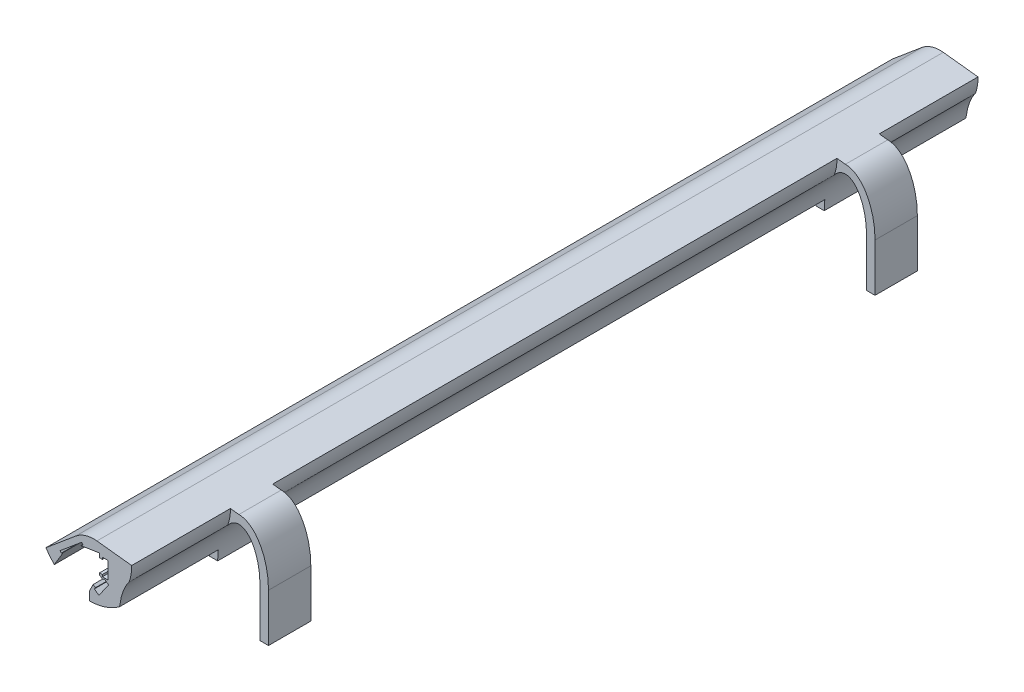
SolidWorks part; units mm, degrees
ref_plane "前视基准面" through (0, 0, 0) normal (0, 0, 1) x (1, 0, 0)
ref_plane "上视基准面" through (0, 0, 0) normal (0, 1, 0) x (1, 0, 0)
ref_plane "右视基准面" through (0, 0, 0) normal (1, 0, 0) x (0, 0, -1)
other "Configuration Table"
sketch "草图1" plane through (0, 0, 0) normal (0, 0, 1) x (1, 0, 0)
  line L0 (0, -18) -> (18, -18) construction
  line L1 (18, -18) -> (18, 0) construction
  line L2 (7.5, -18) -> (10.5, -18)
  line L4 (25.5, -18) -> (25.5, -34.9829)
  line L5 (25.5, -34.9829) -> (28.5, -34.9829)
  line L6 (28.5, -34.9829) -> (28.5, -18)
  line L7 (0, 0) -> (-11.4907, -9.6418)
  line L8 (0, 0) -> (0, -15)
  line L9 (5.2507, -8.584) -> (2.4359, -6.613) construction
  line L10 (0, 0) -> (15, 0) construction
  line L11 (1.8092, -13.4989) -> (-1.7004, -11.0414) construction
  line L12 (4.7829, -8.3) -> (-1.4748, -8.3) construction
  line L13 (4.6248, -8.3) -> (4.6248, -2.3)
  line L14 (4.6248, -8.3) -> (6.6248, -8.3)
  line L15 (4.6248, -2.3) -> (6.6248, -2.3)
  line L16 (6.6248, -8.3) -> (6.6248, -2.3)
  line L25 (5.1998, -8.5483) -> (1.7583, -13.4632)
  line L26 (5.1998, -8.5483) -> (6.8381, -9.6955)
  line L27 (1.7583, -13.4632) -> (3.3966, -14.6104)
  line L28 (6.8381, -9.6955) -> (3.3966, -14.6104)
  line L29 (4.7829, -2.3) -> (-0.818, -2.3) construction
  line L30 (2.1598, -12.8898) -> (1.3407, -12.3162)
  line L31 (1.3407, -12.3162) -> (0, -15)
  line L32 (4.6248, -7.6) -> (3.6248, -7.6)
  line L33 (3.6248, -7.6) -> (3.6248, -8.3)
  line L34 (3.6248, -8.3) -> (4.7983, -9.1217)
  line L35 (4.6248, -3) -> (3.6248, -3)
  line L36 (3.6248, -3) -> (3.6248, -1.5)
  line L37 (0, -15) -> (0, -18)
  line L38 (-9.9586, -8.3562) -> (-2.2981, -1.9284)
  line L39 (-9.9586, -8.3562) -> (-10.4085, -7.82)
  line L40 (-2.2981, -1.9284) -> (-2.7481, -1.3921)
  line L41 (-10.4085, -7.82) -> (-2.7481, -1.3921)
  line L42 (-15.3683, -9.371) -> (-4.8635, -0.5563)
  line L43 (2.6806, 1.7207) -> (18, 0)
  line L44 (-9.1925, -7.7135) -> (-12.3906, -13.0566)
  line L45 (-3.0642, -2.5712) -> (3.6248, -1.5)
  line L46 (4.7983, -9.1217) -> (6.0189, -9.1219)
  circle A0 centre (0, 0) radius 18
  circle A1 centre (0, 0) radius 15
  arc A2 (2.6806, 1.7207) -> (-4.8635, -0.5563) centre (1.5644, -8.2168) ccw
  ellipse E0 centre (18, -18) end of major axis (18, 0) minor radius 10.5 (7.5, -18) -> (28.5, -18) cw
  ellipse E1 centre (18, -18) end of major axis (18, -33) minor radius 7.5 (10.5, -18) -> (25.5, -18) cw
  point P61 (-1.5795, 2.1992)
  dimension "D1" = 30
  dimension "D2" = 3
  dimension "D30" = 10
  dimension "D3" = 3
  dimension "D4" = 15
  dimension "D5" = 15
  dimension "D6" = 50
  dimension "D7" = 35
  dimension "D8" = 0.7
  dimension "D9" = 6
  dimension "D10" = 2
  dimension "D11" = 6
  dimension "D12" = 2
  dimension "D13" = 0.7
  dimension "D14" = 0.7
  dimension "D15" = 0.7
  dimension "D16" = 1
  dimension "D17" = 1
  dimension "D18" = 1
  dimension "D19" = 1.5
  dimension "D20" = 0.7
  dimension "D21" = 3
  dimension "D22" = 0.7
  dimension "D23" = 10
  dimension "D24" = 3
  dimension "D25" = 130
  dimension "D26" = 1
  dimension "D27" = 1
  dimension "D28" = 2
  dimension "D29" = 18
extrude "凸台-拉伸7" add sketch "草图1" along normal blind 150 contours A1 L42 A0 L44 | L7 A1 L44 L38 | A1 E0 L43 A2 L42 L7 L39 L41 L40 L8 L45 L36 L35 L13 L15 L16 L14 L32 L33 L34 L25 L26 L28 | L7 L45 L8 | A1 E1 E0 | A0 E1 A1 E0 | A0 E0 A1 L37 | L31 A1 L27 L25 L30
sketch "草图5" plane through (0, 0, 0) normal (0, 0, 1) x (1, 0, 0)
  line L0 (-15.3683, -9.371) -> (-4.8635, -0.5563) construction
  line L1 (2.6806, 1.7207) -> (18, 0) construction
  line L2 (0, -15) -> (0, -18) construction
  line L3 (0, 0) -> (-11.4907, -9.6418) construction
  line L4 (7.5, -18) -> (10.5, -18)
  line L5 (28.5, -34.9829) -> (28.5, -18)
  line L6 (25.5, -34.9829) -> (28.5, -34.9829)
  line L7 (25.5, -18) -> (25.5, -34.9829)
  line L8 (7.5, -18) -> (10.5, -18)
  line L9 (28.5, -34.9829) -> (28.5, -18)
  line L10 (25.5, -34.9829) -> (28.5, -34.9829)
  line L11 (25.5, -18) -> (25.5, -34.9829)
  line L12 (5.1998, -8.5483) -> (1.7583, -13.4632)
  line L13 (1.7583, -13.4632) -> (3.3966, -14.6104)
  line L14 (3.3966, -14.6104) -> (6.8381, -9.6955)
  line L15 (6.8381, -9.6955) -> (5.1998, -8.5483)
  line L16 (5.1998, -8.5483) -> (1.7583, -13.4632)
  line L17 (1.7583, -13.4632) -> (3.3966, -14.6104)
  line L18 (3.3966, -14.6104) -> (6.8381, -9.6955)
  line L19 (6.8381, -9.6955) -> (5.1998, -8.5483)
  line L20 (6.6248, -8.3) -> (6.6248, -2.3)
  line L21 (6.6248, -2.3) -> (4.6248, -2.3)
  line L22 (4.6248, -2.3) -> (4.6248, -8.3)
  line L23 (4.6248, -8.3) -> (6.6248, -8.3)
  line L24 (6.6248, -8.3) -> (6.6248, -2.3)
  line L25 (6.6248, -2.3) -> (4.6248, -2.3)
  line L26 (4.6248, -2.3) -> (4.6248, -8.3)
  line L27 (4.6248, -8.3) -> (6.6248, -8.3)
  line L28 (-9.9586, -8.3562) -> (-2.2981, -1.9284)
  line L29 (-2.2981, -1.9284) -> (-2.7481, -1.3921)
  line L30 (-2.7481, -1.3921) -> (-10.4085, -7.82)
  line L31 (-10.4085, -7.82) -> (-9.9586, -8.3562)
  line L32 (-9.9586, -8.3562) -> (-2.2981, -1.9284)
  line L33 (-2.2981, -1.9284) -> (-2.7481, -1.3921)
  line L34 (-2.7481, -1.3921) -> (-10.4085, -7.82)
  line L35 (-10.4085, -7.82) -> (-9.9586, -8.3562)
  line L36 (0, 0) -> (0, -15) construction
  line L37 (2.1598, -12.8898) -> (1.3407, -12.3162) construction
  line L38 (1.3407, -12.3162) -> (0, -15) construction
  line L39 (4.6248, -3) -> (3.6248, -3) construction
  line L40 (3.6248, -3) -> (3.6248, -1.5) construction
  line L41 (-3.0642, -2.5712) -> (3.6248, -1.5) construction
  line L42 (4.6248, -7.6) -> (3.6248, -7.6) construction
  line L43 (3.6248, -7.6) -> (3.6248, -8.3) construction
  line L44 (3.6248, -8.3) -> (4.7983, -9.1217) construction
  line L45 (4.7983, -9.1217) -> (6.0189, -9.1219) construction
  line L46 (-9.1925, -7.7135) -> (-12.3906, -13.0566) construction
  line L47 (-15.3683, -9.371) -> (-4.8635, -0.5563)
  line L48 (2.6806, 1.7207) -> (18, 0)
  line L49 (0, -15) -> (0, -18)
  line L50 (0, 0) -> (-11.4907, -9.6418)
  line L51 (0, 0) -> (0, -15)
  line L52 (2.1598, -12.8898) -> (1.3407, -12.3162)
  line L53 (1.3407, -12.3162) -> (0, -15)
  line L54 (4.6248, -3) -> (3.6248, -3)
  line L55 (3.6248, -3) -> (3.6248, -1.5)
  line L56 (-3.0642, -2.5712) -> (3.6248, -1.5)
  line L57 (4.6248, -7.6) -> (3.6248, -7.6)
  line L58 (3.6248, -7.6) -> (3.6248, -8.3)
  line L59 (3.6248, -8.3) -> (4.7983, -9.1217)
  line L60 (4.7983, -9.1217) -> (6.0189, -9.1219)
  line L61 (-9.1925, -7.7135) -> (-12.3906, -13.0566)
  arc A0 (2.6806, 1.7207) -> (-4.8635, -0.5563) centre (1.5644, -8.2168) ccw construction
  circle A1 centre (0, 0) radius 15
  circle A2 centre (0, 0) radius 15
  circle A3 centre (0, 0) radius 18
  circle A4 centre (0, 0) radius 18
  arc A5 (2.6806, 1.7207) -> (-4.8635, -0.5563) centre (1.5644, -8.2168) ccw
  ellipse E2 centre (18, -18) end of major axis (18, 0) minor radius 10.5 (28.5, -18) -> (7.5, -18) ccw
  ellipse E3 centre (18, -18) end of major axis (18, -33) minor radius 7.5 (25.5, -18) -> (10.5, -18) ccw
  ellipse E4 centre (18, -18) end of major axis (18, 0) minor radius 10.5 (28.5, -18) -> (7.5, -18) ccw
  ellipse E5 centre (18, -18) end of major axis (18, -33) minor radius 7.5 (25.5, -18) -> (10.5, -18) ccw
  dimension "D1" = 0
  dimension "D2" = 0
  dimension "D3" = 0
  dimension "D4" = 0
  dimension "D5" = 0
  dimension "D6" = 0
extrude "凸台-拉伸8" add sketch "草图5" along normal blind 15 from offset 100 contours E5 A4 E4 L8 | E5 A4 E4 A2 | E5 L11 L10 L9 E4 A4 | E4 L48 A2
mirror "镜向1" about plane through (0, 0, 0) normal (0, 0, 1) of "凸台-拉伸8", "凸台-拉伸7"
